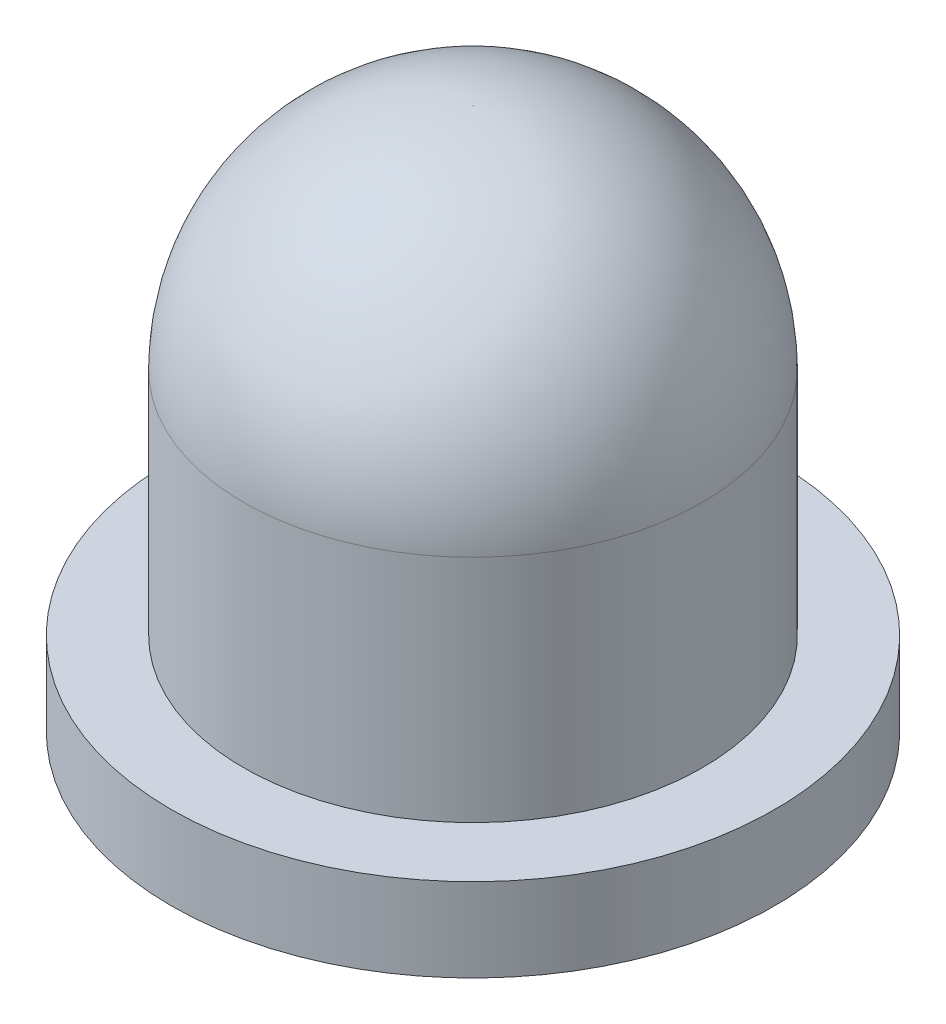
SolidWorks part; units mm, degrees
ref_plane "Alzado" through (0, 0, 0) normal (0, 0, 1) x (1, 0, 0)
ref_plane "Planta" through (0, 0, 0) normal (0, 1, 0) x (1, 0, 0)
ref_plane "Vista lateral" through (0, 0, 0) normal (1, 0, 0) x (0, 0, -1)
sketch "Croquis1" plane through (0, 0, 0) normal (0, 0, 1) x (1, 0, 0)
  line L1 (2.75, -5.5) -> (-2.75, -5.5)
  line L2 (2.75, -5.5) -> (2.75, 0.01)
  line L3 (-2.74, 5.5) -> (-2.75, 5.5)
  line L4 (-2.75, -5.5) -> (-2.75, 5.5)
  line L5 (2.75, -5.5) -> (-2.75, 5.5) construction
  line L6 (2.75, 5.5) -> (-2.75, -5.5) construction
  line L7 (-2.75, -5.5) -> (6.342, -5.5)
  line L8 (-2.75, -5.5) -> (-2.75, -6.5832)
  line L9 (-2.75, -6.5832) -> (6.342, -6.5832)
  line L10 (6.342, -5.5) -> (6.342, -6.5832)
  arc A0 (2.75, 0.01) -> (-2.74, 5.5) centre (-2.74, 0.01) ccw
  point P0 (0, 0)
  dimension "D3" = 5.49
  dimension "D1" = 11
  dimension "D2" = 5.5
revolve "Revolución1" add sketch "Croquis1" angle 360 about L4
sketch "Croquis2" plane through (0, -5.5, 0) normal (0, -1, 0) x (1, 0, 0)
  circle A0 centre (-2.75, 0) radius 7.2344
extrude "Saliente-Extruir1" add sketch "Croquis2" along normal blind 2
